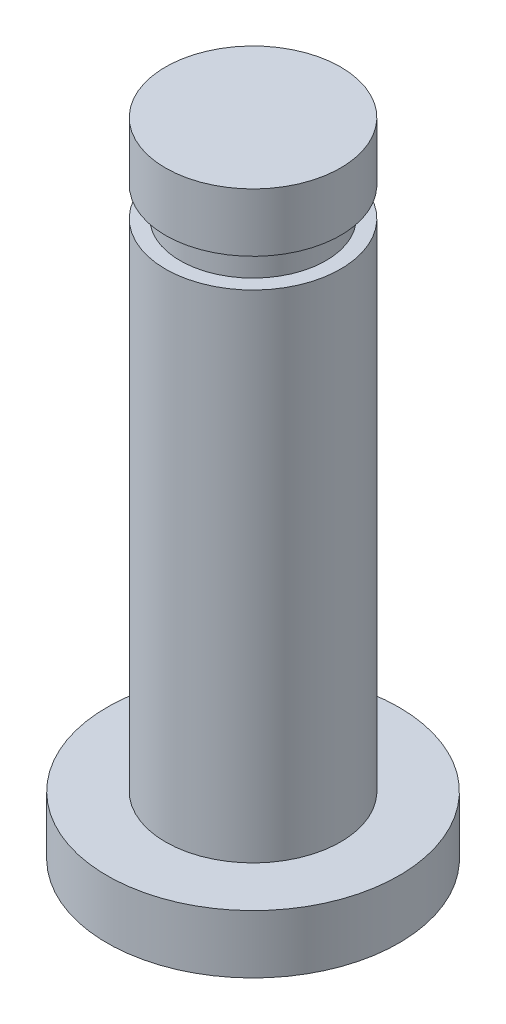
SolidWorks part; units mm, degrees
material "AISI 304"
ref_plane "前视基准面" through (0, 0, 0) normal (0, 0, 1) x (1, 0, 0)
ref_plane "上视基准面" through (0, 0, 0) normal (0, 1, 0) x (1, 0, 0)
ref_plane "右视基准面" through (0, 0, 0) normal (1, 0, 0) x (0, 0, -1)
other "Configuration Table"
sketch "草图1" plane through (0, 0, 0) normal (0, 0, 1) x (1, 0, 0)
  line L0 (3, 0) -> (3, 17)
  line L1 (3, 17) -> (2.5, 17)
  line L2 (2.5, 17) -> (2.5, 18)
  line L3 (2.5, 18) -> (3, 18)
  line L4 (3, 18) -> (3, 20)
  line L5 (3, 20) -> (0, 20)
  line L6 (0, 20) -> (0, -2)
  line L7 (0, -2) -> (5, -2)
  line L8 (5, -2) -> (5, 0)
  line L9 (5, 0) -> (3, 0)
  line L10 (0, 0) -> (0, 10083.7052) construction
  dimension "d" = 6
  dimension "L" = 20
  dimension "lc" = 2
  dimension "D1" = 1
  dimension "D2" = 5
  dimension "k" = 2
  dimension "dk" = 10
revolve "旋转1" add sketch "草图1" angle 360 about L10
equation "\"lc@草图1\" = \"d@草图1\" / 3"
